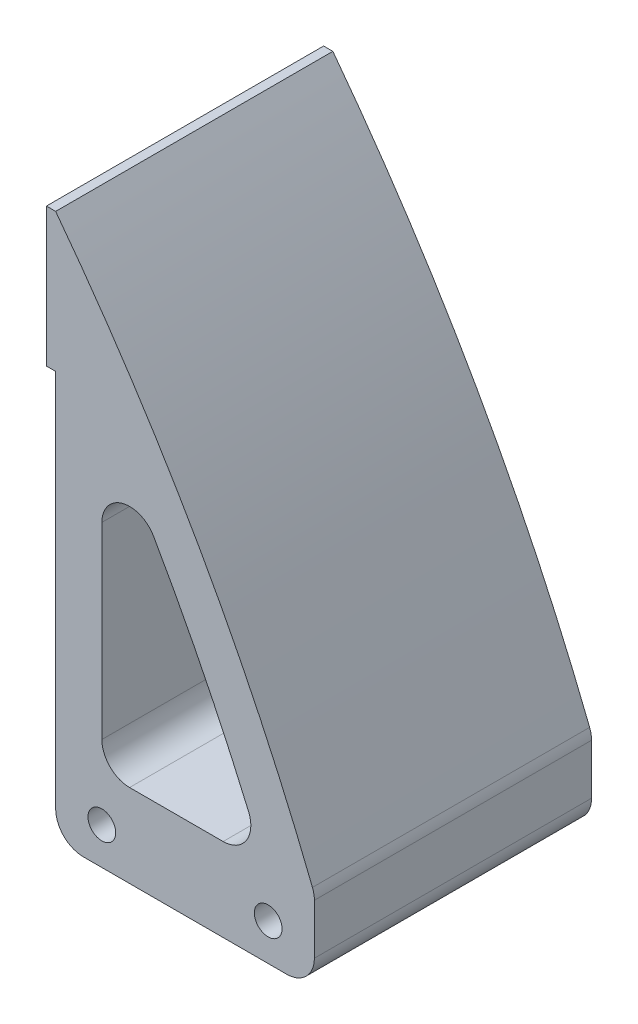
SolidWorks part; units mm, degrees
ref_plane "前视基准面" through (0, 0, 0) normal (0, 0, 1) x (1, 0, 0)
ref_plane "上视基准面" through (0, 0, 0) normal (0, 1, 0) x (1, 0, 0)
ref_plane "右视基准面" through (0, 0, 0) normal (1, 0, 0) x (0, 0, -1)
other "Configuration Table"
sketch "草图1" plane through (0, 0, 0) normal (0, 0, 1) x (1, 0, 0)
  line L0 (0, 6) -> (0, -6) construction
  line L1 (-14, 6) -> (14, 6)
  line L2 (-14, 6) -> (-14, -6)
  line L3 (-14, -6) -> (14, -6)
  line L4 (14, 6) -> (14, -6)
  line L5 (-14, 6) -> (14, -6) construction
  line L6 (-14, -6) -> (14, 6) construction
  line L7 (-14, 6) -> (-14, 56)
  line L8 (-9, 6) -> (-9, 40.0975)
  line L10 (-14, 56) -> (-15, 56)
  line L11 (-14, 56) -> (-14, 41)
  line L12 (-14, 41) -> (-15, 41)
  line L13 (-15, 56) -> (-15, 41)
  circle A0 centre (-9, 1) radius 1.5
  circle A1 centre (9, 1) radius 1.5
  arc A2 (-14, 56) -> (14, 6) centre (-181.5127, -70.6471) cw
  arc A3 (-9, 40.0975) -> (8.6194, 6) centre (-181.5127, -70.6471) cw
  arc A4 (-9, 40.0975) -> (9.3449, 4.1751) centre (-181.5127, -70.6471) cw construction
  point P0 (0, 0)
  point P18 (8.6194, 6)
  dimension "D2" = 3
  dimension "D7" = 210
  dimension "D1" = 12
  dimension "D3" = 5
  dimension "D4" = 5
  dimension "D5" = 28
  dimension "D6" = 50
  dimension "D9" = 1
  dimension "D10" = 15
  dimension "D8" = 5
extrude "凸台-拉伸1" add sketch "草图1" along normal blind 30 contours L8 A3 L1 A2 L7 | L10 L13 L12 L7 | L4 L1 L2 L3 A0 A1
fillet "圆角1" radius 3 5 edges at (14, -6, 15) (-14, -6, 15) (8.6194, 6, 15) (-9, 40.0975, 15) (-9, 6, 15)
sketch "草图2" plane through (0, 0, 30) normal (0, 0, 1) x (1, 0, 0)
  line L0 (-14, -3) -> (14, -3)
  line L6 (-11, -6) -> (11, -6)
  line L7 (14, -3) -> (14, 6)
  line L8 (-14, 56) -> (-15, 56)
  line L9 (-15, 56) -> (-15, 41)
  line L10 (-15, 41) -> (-14, 41)
  line L11 (-14, 41) -> (-14, -3)
  line L12 (-11, -6) -> (11, -6)
  line L13 (14, -3) -> (14, 6)
  line L14 (-14, 56) -> (-15, 56)
  line L15 (-15, 56) -> (-15, 41)
  line L16 (-15, 41) -> (-14, 41)
  line L17 (-14, 41) -> (-14, -3)
  arc A3 (11, -6) -> (14, -3) centre (11, -3) ccw
  arc A4 (14, 6) -> (-14, 56) centre (-181.5127, -70.6471) ccw
  arc A5 (-14, -3) -> (-11, -6) centre (-11, -3) ccw
  arc A6 (11, -6) -> (14, -3) centre (11, -3) ccw
  arc A7 (14, 6) -> (-14, 56) centre (-181.5127, -70.6471) ccw
  arc A8 (-14, -3) -> (-11, -6) centre (-11, -3) ccw
  line M11 (-11, -6) -> (11, -6)
  arc M12 (11, -6) -> (14, -3) centre (11, -3) ccw
  arc M19 (-14, -3) -> (-11, -6) centre (-11, -3) ccw
  dimension "D2" = 3
  dimension "D1" = 0
extrude "切除-拉伸1" cut sketch "草图2" against normal through all contours L0 M19 M11 M12
fillet "圆角2" radius 3 3 edges at (14, -3, 15) (14, 6, 15) (-14, -3, 15)
